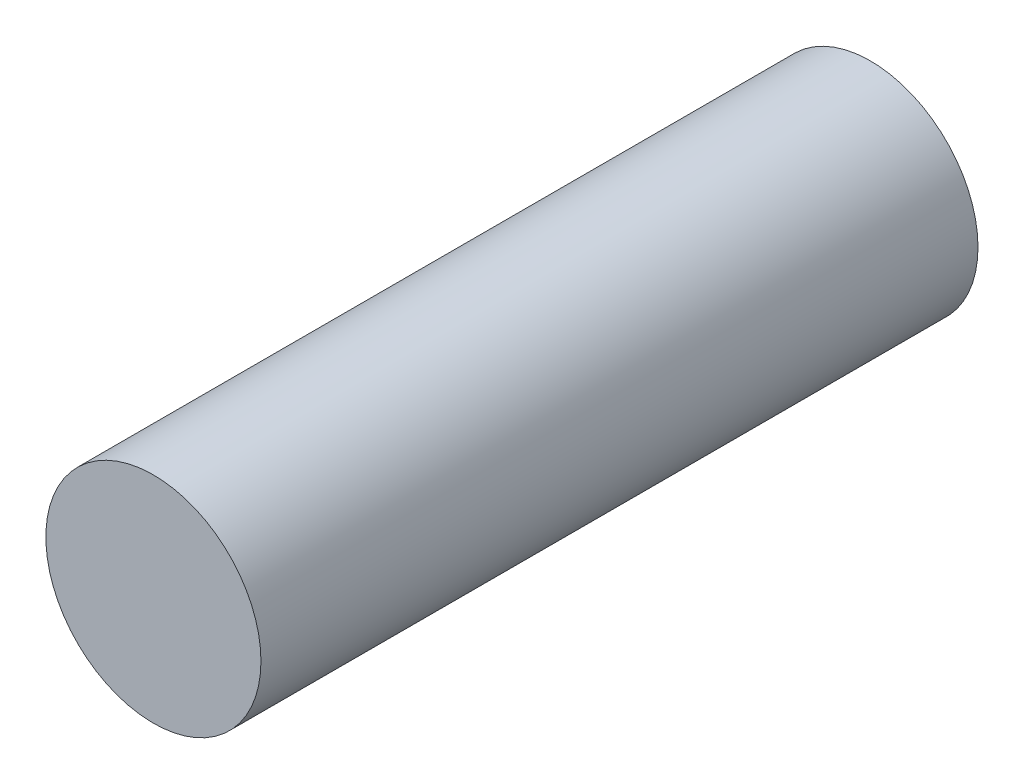
SolidWorks part; units mm, degrees
ref_plane "Спереди" through (0, 0, 0) normal (0, 0, 1) x (1, 0, 0)
ref_plane "Сверху" through (0, 0, 0) normal (0, 1, 0) x (1, 0, 0)
ref_plane "Справа" through (0, 0, 0) normal (1, 0, 0) x (0, 0, -1)
sketch "Эскиз1" plane through (0, 0, 0) normal (0, 0, 1) x (1, 0, 0)
  circle A0 centre (0, 0) radius 9
  dimension "D1" = 18
extrude "Бобышка-Вытянуть1" add sketch "Эскиз1" along normal blind 60
